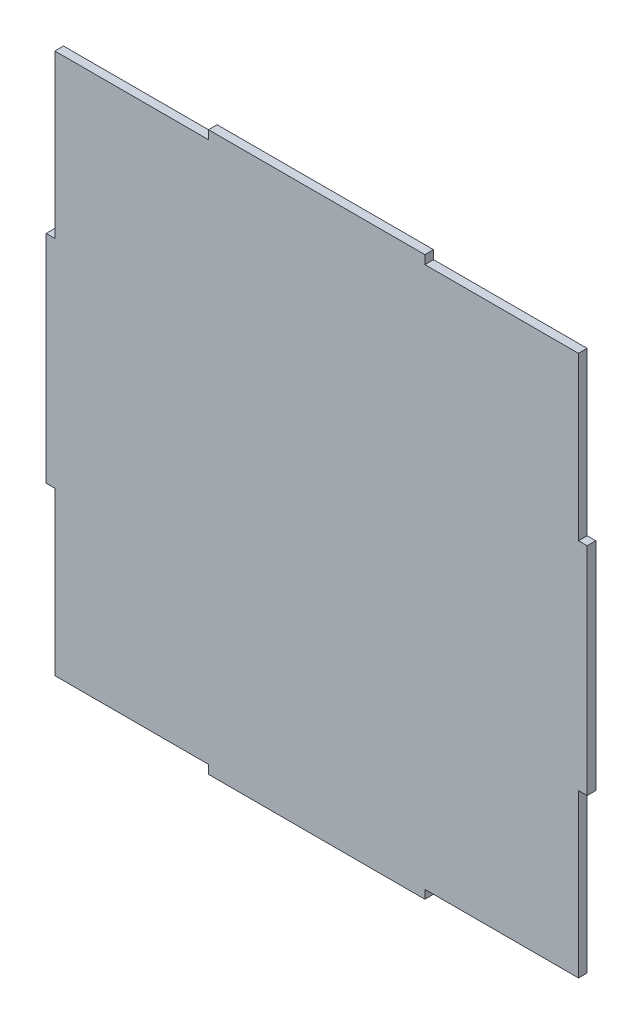
SolidWorks part; units mm, degrees
ref_plane "Front Plane" through (0, 0, 0) normal (0, 0, 1) x (1, 0, 0)
ref_plane "Top Plane" through (0, 0, 0) normal (0, 1, 0) x (1, 0, 0)
ref_plane "Right Plane" through (0, 0, 0) normal (1, 0, 0) x (0, 0, -1)
sketch "Sketch1" plane through (0, 0, 0) normal (0, 0, 1) x (1, 0, 0)
  line L0 (-50, 128.9092) -> (-50, 124.9092)
  line L1 (-50, 124.9092) -> (-121, 124.9092)
  line L2 (-121, 124.9092) -> (-121, 49.9092)
  line L3 (-121, 49.9092) -> (-125, 49.9092)
  line L4 (-125, 49.9092) -> (-125, -50.0908)
  line L5 (-125, -50.0908) -> (-121, -50.0908)
  line L6 (-121, -50.0908) -> (-121, -125.0908)
  line L7 (-121, -125.0908) -> (-50, -125.0908)
  line L8 (-50, -125.0908) -> (-50, -129.0908)
  line L9 (-50, -129.0908) -> (50, -129.0908)
  line L10 (50, -129.0908) -> (50, -125.0908)
  line L11 (50, -125.0908) -> (121, -125.0908)
  line L12 (121, -125.0908) -> (121, -50.0908)
  line L13 (121, -50.0908) -> (125, -50.0908)
  line L14 (125, -50.0908) -> (125, 49.9092)
  line L15 (125, 49.9092) -> (121, 49.9092)
  line L16 (121, 49.9092) -> (121, 124.9092)
  line L17 (121, 124.9092) -> (50, 124.9092)
  line L18 (50, 124.9092) -> (50, 128.9092)
  line L19 (50, 128.9092) -> (-50, 128.9092)
extrude "Boss-Extrude1" add sketch "Sketch1" along normal blind 4
